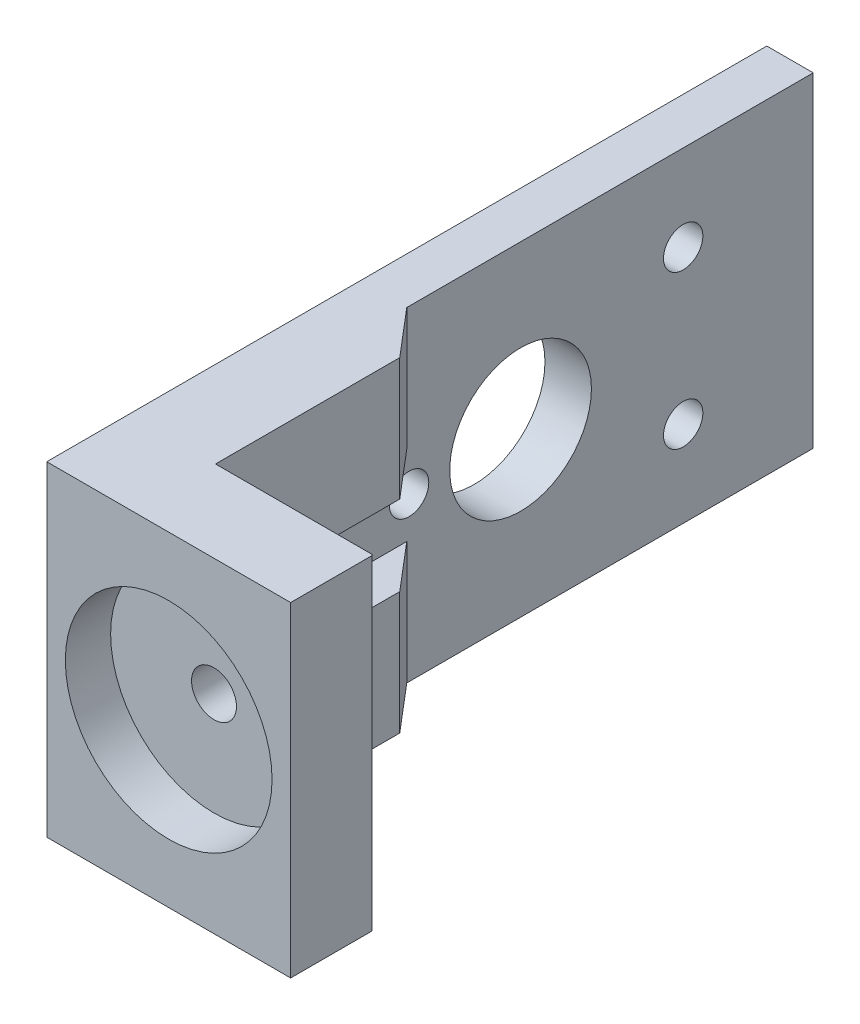
SolidWorks part; units mm, degrees
ref_plane "Front Plane" through (0, 0, 0) normal (0, 0, 1) x (1, 0, 0)
ref_plane "Top Plane" through (0, 0, 0) normal (0, 1, 0) x (1, 0, 0)
ref_plane "Right Plane" through (0, 0, 0) normal (1, 0, 0) x (0, 0, -1)
sketch "Sketch1" plane through (0, 0, 0) normal (0, 1, 0) x (1, 0, 0)
  line L1 (0, 78.74) -> (5.08, 78.74)
  line L2 (0, 78.74) -> (0, 0)
  line L3 (0, 0) -> (5.08, 0)
  line L4 (5.08, 78.74) -> (5.08, 0)
  line L5 (5.08, 0) -> (26.67, 0)
  line L6 (5.08, 0) -> (5.08, 8.89)
  line L7 (5.08, 8.89) -> (26.67, 8.89)
  line L8 (26.67, 0) -> (26.67, 8.89)
  dimension "D1" = 21.59
  dimension "D2" = 8.89
  dimension "D3" = 0
  dimension "D4" = 5.08
  dimension "D5" = 78.74
  dimension "D6" = 0
extrude "Boss-Extrude1" add sketch "Sketch1" along normal blind 35.56 contours L4 L1 L2 L3 | L5 L8 L7 L4
sketch "Sketch2" plane through (0, 0, 0) normal (0, 0, 1) x (1, 0, 0)
  line L0 (26.67, 17.78) -> (0, 17.78) construction
  line L1 (26.67, 35.56) -> (26.67, 0) construction
  line L2 (0, 35.56) -> (0, 0) construction
  circle A0 centre (13.335, 17.78) radius 11.303
  point P0 (13.335, 17.78)
  dimension "D1" = 22.606
extrude "Cut-Extrude1" cut sketch "Sketch2" against normal blind 4.953
sketch "Sketch3" plane through (0, 0, -4.953) normal (0, 0, 1) x (1, 0, 0)
  point P0 (13.335, 17.78)
hole_wizard "#8 Clearance Hole1" positions "Sketch3" profile "Sketch4" hole size "#8" standard "ANSI Inch" end condition up to next
sketch "Sketch4" plane through (13.335, 17.78, -4.953) normal (1, 0, 0) x (0, -1, 0)
  line L0 (0, 0) -> (0, 3.937)
  line L1 (0, 3.937) -> (2.4574, 3.937)
  line L2 (2.4574, 3.937) -> (2.4574, 0)
  line L5 (2.4574, 0) -> (0, 0)
  line L11 (0, -6.35) -> (0, 107.95) construction
  dimension "Thru Hole Dia." = 4.9149
  dimension "Thru Hole Depth" = 3.937
sketch "Sketch5" plane through (5.08, 0, 0) normal (1, 0, 0) x (0, 0, -1)
  line L0 (0, 17.78) -> (78.74, 17.78) construction
  line L1 (0, 35.56) -> (0, 0) construction
  line L2 (78.74, 35.56) -> (78.74, 0) construction
  circle A0 centre (46.736, 17.78) radius 7.747
  point P6 (46.736, 17.78)
  dimension "D2" = 15.494
  dimension "D1" = 46.736
extrude "Cut-Extrude4" cut sketch "Sketch5" against normal up to next contours A0 | L0 A0
sketch "Sketch15" plane through (5.08, 0, 0) normal (1, 0, 0) x (0, 0, -1)
  line L0 (64.516, 35.56) -> (64.516, 0) construction
  line L1 (78.74, 35.56) -> (8.89, 35.56) construction
  line L2 (78.74, 0) -> (8.89, 0) construction
  line L3 (0, 17.78) -> (78.74, 17.78) construction
  point P0 (46.736, 17.78)
  point P8 (64.516, 26.162)
  point P9 (64.516, 9.398)
  point P10 (34.544, 17.78)
  dimension "D1" = 17.78
  dimension "D2" = 9.398
  dimension "D3" = 9.398
  dimension "D4" = 12.192
hole_wizard "#6 Clearance Hole1" positions "Sketch15" profile "Sketch16" hole size "#6" standard "ANSI Inch" end condition up to next
sketch "Sketch16" plane through (5.08, 17.78, -34.544) normal (0, 1, 0) x (0, 0, -1)
  line L0 (0, 0) -> (0, 5.08)
  line L1 (0, 5.08) -> (2.1526, 5.08)
  line L2 (2.1526, 5.08) -> (2.1526, 0)
  line L5 (2.1526, 0) -> (0, 0)
  line L11 (0, -6.35) -> (0, 107.95) construction
  dimension "Thru Hole Dia." = 4.3053
  dimension "Thru Hole Depth" = 5.08
sketch "Sketch17" plane through (0, 35.56, 0) normal (0, 1, 0) x (1, 0, 0)
  line L0 (5.08, 8.89) -> (5.08, 34.29)
  line L1 (5.08, 0) -> (5.08, 78.74) construction
  line L2 (5.08, 34.29) -> (26.67, 8.89)
  line L3 (26.67, 0) -> (26.67, 8.89) construction
  line L4 (5.08, 8.89) -> (26.67, 8.89) construction
  line L5 (26.67, 8.89) -> (5.08, 8.89)
  dimension "D1" = 25.4
extrude "Boss-Extrude3" add sketch "Sketch17" against normal blind 13.3985
sketch "Sketch18" plane through (0, 0, 0) normal (0, -1, 0) x (1, 0, 0)
  line L0 (26.67, -8.89) -> (5.08, -8.89)
  line L1 (5.08, -8.89) -> (5.08, -34.29)
  line L2 (5.08, -78.74) -> (5.08, -8.89) construction
  line L3 (5.08, -34.29) -> (26.67, -8.89)
  dimension "D1" = 25.4
extrude "Boss-Extrude4" add sketch "Sketch18" against normal blind 13.3985
sketch "Sketch19" plane through (5.08, 0, 0) normal (1, 0, 0) x (0, 0, -1)
  line L0 (0, 17.78) -> (78.74, 17.78) construction
  point P0 (31.496, 17.78)
  dimension "D1" = 15.24
sketch "Sketch21" plane through (0, 35.56, 0) normal (0, 1, 0) x (1, 0, 0)
  circle A0 centre (44.9379, 45.023) radius 38.1
  dimension "D1" = 76.2
extrude "Cut-Extrude5" cut sketch "Sketch21" against normal through all contours A0
sketch "Sketch22" plane through (0, 35.56, 0) normal (0, 1, 0) x (1, 0, 0)
  line L1 (9.4408, 39.6984) -> (27.2695, 39.6984)
  line L2 (9.4408, 39.6984) -> (9.4408, 9.0143)
  line L3 (9.4408, 9.0143) -> (27.2695, 9.0143)
  line L4 (27.2695, 39.6984) -> (27.2695, 9.0143)
extrude "Cut-Extrude6" cut sketch "Sketch22" against normal blind 121.92
